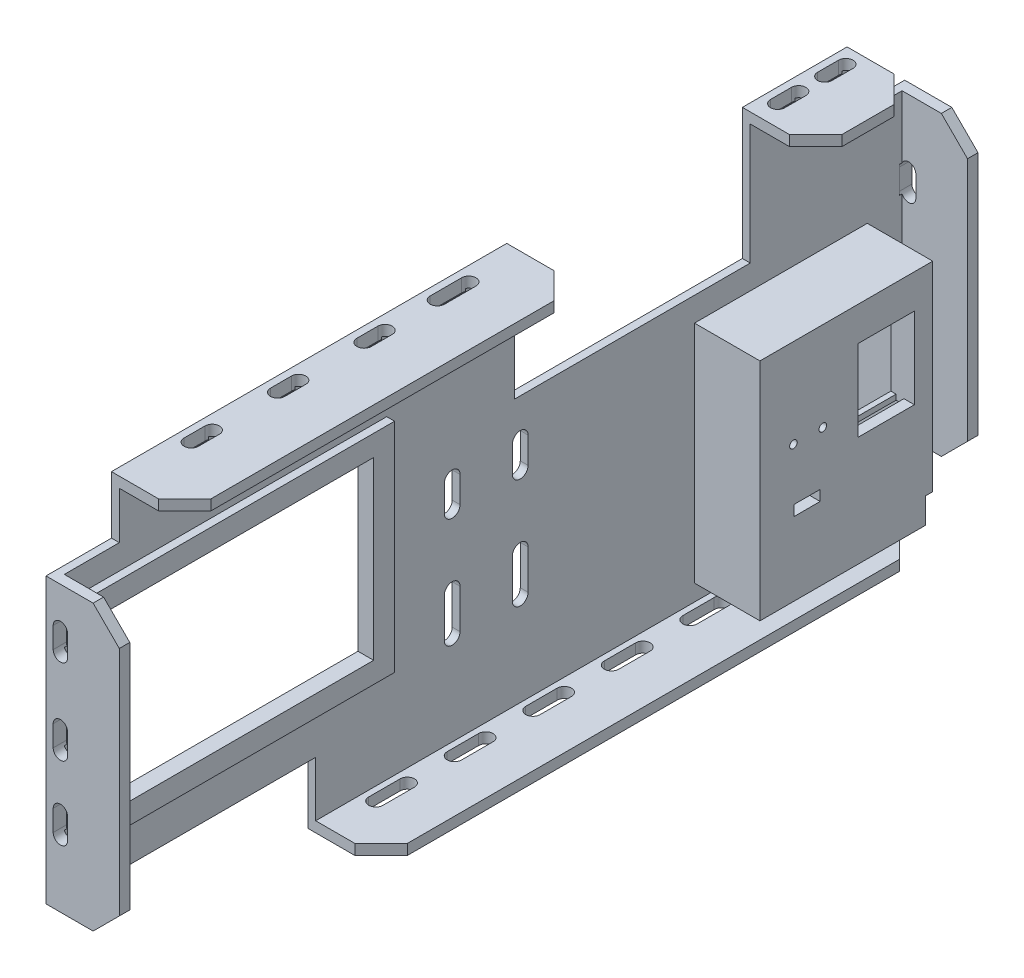
SolidWorks part; units mm, degrees
ref_plane "前视基准面" through (0, 0, 0) normal (0, 0, 1) x (1, 0, 0)
ref_plane "上视基准面" through (0, 0, 0) normal (0, 1, 0) x (1, 0, 0)
ref_plane "右视基准面" through (0, 0, 0) normal (1, 0, 0) x (0, 0, -1)
other "Configuration Table"
sketch "草图1" plane through (0, 0, 0) normal (1, 0, 0) x (0, 0, -1)
  line L0 (10, 87) -> (70, 87)
  line L1 (0, 0) -> (80, 0)
  line L2 (0, 0) -> (0, 97)
  line L3 (0, 97) -> (80, 97)
  line L4 (80, 0) -> (80, 97)
  line L5 (70, 10) -> (70, 87)
  line L6 (10, 10) -> (70, 10)
  line L7 (10, 10) -> (10, 87)
  dimension "D1" = 97
  dimension "D2" = 80
  dimension "D3" = 10
extrude "凸台-拉伸1" add sketch "草图1" along normal blind 6
sketch "草图2" plane through (6, 0, 0) normal (1, 0, 0) x (0, 0, -1)
  line L0 (80, 97) -> (0, 97) construction
  line L1 (10, 87) -> (70, 87)
  line L2 (10, 87) -> (10, 97)
  line L3 (10, 97) -> (70, 97)
  line L4 (70, 87) -> (70, 97)
  line L5 (0, 0) -> (80, 0) construction
  line L6 (10, 10) -> (70, 10)
  line L7 (10, 10) -> (10, 0)
  line L8 (10, 0) -> (70, 0)
  line L9 (70, 10) -> (70, 0)
extrude "凸台-拉伸2" add sketch "草图2" along normal blind 25
sketch "草图3" plane through (31, 0, 0) normal (1, 0, 0) x (0, 0, -1)
  line L1 (10, 87) -> (70, 87)
  line L2 (10, 87) -> (10, 10)
  line L3 (10, 10) -> (70, 10)
  line L4 (70, 87) -> (70, 10)
extrude "凸台-拉伸3" add sketch "草图3" against normal blind 4
sketch "草图4" plane through (27, 0, 0) normal (-1, 0, 0) x (0, 0, 1)
  line L0 (-70, 10) -> (-70, 87) construction
  line L1 (-66, 46) -> (-44.5, 46)
  line L2 (-66, 46) -> (-66, 77)
  line L3 (-66, 77) -> (-44.5, 77)
  line L4 (-44.5, 46) -> (-44.5, 77)
  line L5 (-70, 87) -> (-10, 87) construction
  dimension "D1" = 4
  dimension "D2" = 21.5
  dimension "D3" = 31
  dimension "D4" = 10
extrude "切除-拉伸1" cut sketch "草图4" against normal blind 4
sketch "草图5" plane through (27, 0, 0) normal (-1, 0, 0) x (0, 0, 1)
  line L0 (-66, 46) -> (-44.5, 46) construction
  line L1 (-44.5, 46) -> (-44.5, 77) construction
  line L2 (-66, 77) -> (-66, 46) construction
  line L3 (-44.5, 77) -> (-66, 77) construction
  line L4 (-66, 46) -> (-44.5, 46)
  line L5 (-44.5, 46) -> (-44.5, 77)
  line L6 (-66, 77) -> (-66, 46)
  line L7 (-44.5, 77) -> (-66, 77)
  line L8 (-68, 44) -> (-42.5, 44)
  line L9 (-42.5, 44) -> (-42.5, 79)
  line L10 (-42.5, 79) -> (-68, 79)
  line L11 (-68, 79) -> (-68, 44)
  dimension "D1" = 2
extrude "凸台-拉伸4" add sketch "草图5" along normal blind 5
sketch "草图6" plane through (0, 44, 0) normal (0, -1, 0) x (1, 0, 0)
  line L0 (22, -68) -> (27, -68) construction
  line L1 (24, -44.5) -> (27, -44.5)
  line L2 (24, -44.5) -> (24, -66)
  line L3 (24, -66) -> (27, -66)
  line L4 (27, -44.5) -> (27, -66)
  line L5 (22, -42.5) -> (27, -42.5) construction
  line L6 (22, -68) -> (22, -42.5) construction
  dimension "D1" = 2
  dimension "D2" = 2
  dimension "D3" = 2
  dimension "D4" = 3
extrude "切除-拉伸2" cut sketch "草图6" against normal blind 37
sketch "草图7" plane through (27, 0, 0) normal (-1, 0, 0) x (0, 0, 1)
  line L0 (-42.5, 44) -> (-42.5, 79) construction
  line L1 (-34.5, 44) -> (-16.3, 44)
  line L2 (-34.5, 44) -> (-34.5, 74.1)
  line L3 (-34.5, 74.1) -> (-16.3, 74.1)
  line L4 (-16.3, 44) -> (-16.3, 74.1)
  dimension "D1" = 18.2
  dimension "D2" = 30.1
  dimension "D3" = 8
  dimension "D4" = 44
extrude "切除-拉伸3" cut sketch "草图7" against normal blind 1.5
sketch "草图8" plane through (28.5, 0, 0) normal (-1, 0, 0) x (0, 0, 1)
  line L0 (-34.5, 44) -> (-16.3, 44) construction
  line L1 (-34.5, 44) -> (-16.3, 44) construction
  line L2 (-34.5, 74.1) -> (-34.5, 44) construction
  line L3 (-16.3, 44) -> (-16.3, 74.1) construction
  circle A0 centre (-31, 56) radius 1.45
  circle A1 centre (-19.8, 56) radius 1.45
  dimension "D1" = 12
  dimension "D3" = 2.9
  dimension "D4" = 2.9
  dimension "D2" = 12
  dimension "D5" = 3.5
  dimension "D6" = 3.5
extrude "切除-拉伸5" cut sketch "草图8" against normal blind 4.5
fillet "圆角1" radius 3 1 edges at (0, 0, -40)
fillet "圆角2" radius 3 1 edges at (0, 97, -40)
sketch "草图9" plane through (0, 97, 0) normal (0, 1, 0) x (1, 0, 0)
  line L0 (0, 0) -> (0, 80) construction
  line L1 (31, 70) -> (6, 70) construction
  circle A0 centre (6.2, 54) radius 2.75
  circle A1 centre (6.2, 46) radius 2.75
  circle A2 centre (6.2, 36) radius 2.75
  circle A3 centre (6.2, 28) radius 2.75
  dimension "D1" = 6.2
  dimension "D3" = 5.5
  dimension "D2" = 16
  dimension "D4" = 8
  dimension "D5" = 10
  dimension "D6" = 8
extrude "切除-拉伸6" cut sketch "草图9" against normal blind 10
sketch "草图10" plane through (0, 0, 0) normal (-1, 0, 0) x (0, 0, 1)
  line L1 (-70, 87) -> (-10, 87)
  line L2 (-70, 87) -> (-70, 92)
  line L3 (-70, 92) -> (-10, 92)
  line L4 (-10, 87) -> (-10, 92)
  dimension "D1" = 5
extrude "切除-拉伸7" cut sketch "草图10" against normal blind 20
sketch "草图11" plane through (0, 0, 0) normal (-1, 0, 0) x (0, 0, 1)
  line L0 (-10, 92) -> (-10, 10) construction
  line L1 (-70, 10) -> (-10, 10)
  line L2 (-70, 10) -> (-70, 20)
  line L3 (-70, 20) -> (-10, 20)
  line L4 (-10, 10) -> (-10, 20)
  dimension "D1" = 10
extrude "凸台-拉伸5" add sketch "草图11" against normal blind 5
sketch "草图12" plane through (0, 0, 0) normal (-1, 0, 0) x (0, 0, 1)
  line L0 (0, 0) -> (-80, 0) construction
  line L1 (0, 94) -> (0, 3) construction
  circle A0 centre (-61, 14) radius 2.7
  circle A1 centre (-46, 14) radius 2.7
  circle A2 centre (-30, 14) radius 2.7
  circle A3 centre (-15, 14) radius 2.7
  dimension "D1" = 14
  dimension "D2" = 5.4
  dimension "D4" = 5.4
  dimension "D5" = 5.4
  dimension "D6" = 5.4
  dimension "D3" = 15
  dimension "D7" = 15
  dimension "D8" = 15
  dimension "D9" = 16
extrude "切除-拉伸8" cut sketch "草图12" against normal blind 5
sketch "草图13" plane through (0, 0, -70) normal (0, 0, -1) x (-1, 0, 0)
  line L1 (-6, 10) -> (-27, 10)
  line L2 (-6, 10) -> (-6, 7)
  line L3 (-6, 7) -> (-27, 7)
  line L4 (-27, 10) -> (-27, 7)
  dimension "D1" = 3
extrude "切除-拉伸9" cut sketch "草图13" against normal blind 80
sketch "草图14" plane through (0, 0, 0) normal (-1, 0, 0) x (0, 0, 1)
  line L1 (-121.2338, 126.064) -> (53.7432, 126.064)
  line L2 (-121.2338, 126.064) -> (-121.2338, -60.5781)
  line L3 (-121.2338, -60.5781) -> (53.7432, -60.5781)
  line L4 (53.7432, 126.064) -> (53.7432, -60.5781)
extrude "切除-拉伸11" cut sketch "草图14" against normal blind 22
sketch "草图15" plane through (22, 0, 0) normal (-1, 0, 0) x (0, 0, 1)
  line L4 (-10, 87) -> (-10, 97)
  line L5 (-10, 97) -> (-70, 97)
  line L6 (-70, 97) -> (-70, 87)
  line L7 (-70, 87) -> (-10, 87)
  line L8 (-10, 87) -> (-10, 97)
  line L9 (-10, 97) -> (-70, 97)
  line L10 (-70, 97) -> (-70, 87)
  line L11 (-70, 87) -> (-10, 87)
  line L12 (-70, 0) -> (-10, 0)
  line L13 (-10, 0) -> (-10, 7)
  line L14 (-10, 7) -> (-70, 7)
  line L15 (-70, 7) -> (-70, 0)
  line L16 (-70, 0) -> (-10, 0)
  line L17 (-10, 0) -> (-10, 7)
  line L18 (-10, 7) -> (-70, 7)
  line L19 (-70, 7) -> (-70, 0)
  dimension "D1" = 0
  dimension "D2" = 0
extrude "切除-拉伸12" cut sketch "草图15" against normal blind 22
sketch "草图19" plane through (31, 0, 0) normal (1, 0, 0) x (0, 0, -1)
  line L0 (86.2882, 145.23) -> (-233.7118, 145.23)
  line L1 (90.2882, -6.27) -> (-237.7118, -6.27)
  line L2 (90.2882, -6.27) -> (90.2882, 149.23)
  line L3 (90.2882, 149.23) -> (-237.7118, 149.23)
  line L4 (-237.7118, -6.27) -> (-237.7118, 149.23)
  line L5 (-233.7118, -2.27) -> (-233.7118, 145.23)
  line L6 (86.2882, -2.27) -> (-233.7118, -2.27)
  line L7 (86.2882, -2.27) -> (86.2882, 145.23)
  dimension "D1" = 155.5
  dimension "D2" = 328
  dimension "D3" = 4
extrude "凸台-拉伸6" add sketch "草图19" against normal blind 28 separate body
sketch "草图20" plane through (31, 0, 0) normal (1, 0, 0) x (0, 0, -1)
  line L0 (73, 90) -> (7, 90)
  line L1 (7, 90) -> (7, 4)
  line L2 (7, 4) -> (73, 4)
  line L3 (73, 4) -> (73, 90)
  line L4 (70, 7) -> (70, 87)
  line L5 (70, 87) -> (10, 87)
  line L6 (10, 87) -> (10, 7)
  line L7 (10, 7) -> (70, 7)
  line L8 (70, 7) -> (70, 87)
  line L9 (70, 87) -> (10, 87)
  line L10 (10, 87) -> (10, 7)
  line L11 (10, 7) -> (70, 7)
  dimension "D1" = 0
  dimension "D2" = 3
extrude "凸台-拉伸7" add sketch "草图20" against normal blind 28
sketch "草图21" plane through (3, 0, 0) normal (-1, 0, 0) x (0, 0, 1)
  line L4 (-90.2882, 149.23) -> (-90.2882, -6.27)
  line L5 (-90.2882, -6.27) -> (237.7118, -6.27)
  line L6 (237.7118, -6.27) -> (237.7118, 149.23)
  line L7 (237.7118, 149.23) -> (-90.2882, 149.23)
  line L8 (-90.2882, 149.23) -> (-90.2882, -6.27)
  line L9 (-90.2882, -6.27) -> (237.7118, -6.27)
  line L10 (237.7118, -6.27) -> (237.7118, 149.23)
  line L11 (237.7118, 149.23) -> (-90.2882, 149.23)
  line L12 (-73, 90) -> (-73, 4)
  line L13 (-73, 4) -> (-7, 4)
  line L14 (-7, 4) -> (-7, 90)
  line L15 (-7, 90) -> (-73, 90)
  line L16 (-73, 90) -> (-73, 4)
  line L17 (-73, 4) -> (-7, 4)
  line L18 (-7, 4) -> (-7, 90)
  line L19 (-7, 90) -> (-73, 90)
  dimension "D1" = 0
  dimension "D2" = 0
extrude "凸台-拉伸8" add sketch "草图21" against normal blind 3
sketch "草图22" plane through (6, 0, 0) normal (1, 0, 0) x (0, 0, -1)
  line L0 (-85.5598, 84.73) -> (-85.5598, 74.73) construction
  line L1 (-82.5598, 84.73) -> (-82.5598, 74.73)
  line L2 (-88.5598, 84.73) -> (-88.5598, 74.73)
  line L3 (-85.5598, 32.73) -> (-85.5598, 47.73) construction
  line L4 (-88.5598, 32.73) -> (-88.5598, 47.73)
  line L5 (-82.5598, 32.73) -> (-82.5598, 47.73)
  line L6 (-59.5598, 74.7258) -> (-59.5598, 84.7258) construction
  line L7 (-62.5598, 74.7258) -> (-62.5598, 84.7258)
  line L8 (-56.5598, 74.7258) -> (-56.5598, 84.7258)
  line L9 (-59.5598, 32.73) -> (-59.5598, 47.73) construction
  line L10 (-62.5598, 32.73) -> (-62.5598, 47.73)
  line L11 (-56.5598, 32.73) -> (-56.5598, 47.73)
  line L12 (-233.7118, -2.27) -> (86.2882, -2.27) construction
  arc A0 (-82.5598, 84.73) -> (-88.5598, 84.73) centre (-85.5598, 84.73) ccw
  arc A1 (-88.5598, 74.73) -> (-82.5598, 74.73) centre (-85.5598, 74.73) ccw
  arc A2 (-88.5598, 32.73) -> (-82.5598, 32.73) centre (-85.5598, 32.73) ccw
  arc A3 (-82.5598, 47.73) -> (-88.5598, 47.73) centre (-85.5598, 47.73) ccw
  arc A4 (-62.5598, 74.7258) -> (-56.5598, 74.7258) centre (-59.5598, 74.7258) ccw
  arc A5 (-56.5598, 84.7258) -> (-62.5598, 84.7258) centre (-59.5598, 84.7258) ccw
  arc A6 (-62.5598, 32.73) -> (-56.5598, 32.73) centre (-59.5598, 32.73) ccw
  arc A7 (-56.5598, 47.73) -> (-62.5598, 47.73) centre (-59.5598, 47.73) ccw
  point P2 (-85.5598, 79.73)
  point P7 (-85.5598, 40.23)
  point P14 (-59.5598, 79.7258)
  point P21 (-59.5598, 40.23)
  dimension "D4" = 52
  dimension "D7" = 3
  dimension "D8" = 3
  dimension "D9" = 3
  dimension "D10" = 3
  dimension "D1" = 26
  dimension "D2" = 10
  dimension "D3" = 10
  dimension "D5" = 15
  dimension "D6" = 15
  dimension "D11" = 35
extrude "切除-拉伸13" cut sketch "草图22" against normal blind 3
sketch "草图24" plane through (6, 0, 0) normal (1, 0, 0) x (0, 0, -1)
  line L0 (-88.5598, 47.73) -> (-88.5598, 32.73) construction
  line L1 (-118.5598, 42.73) -> (-223.8598, 42.73)
  line L2 (-118.5598, 42.73) -> (-118.5598, 109.83)
  line L3 (-118.5598, 109.83) -> (-223.8598, 109.83)
  line L4 (-223.8598, 42.73) -> (-223.8598, 109.83)
  line L5 (-233.7118, -2.27) -> (86.2882, -2.27) construction
  dimension "D1" = 105.3
  dimension "D2" = 67.1
  dimension "D3" = 30
  dimension "D4" = 45
extrude "切除-拉伸15" cut sketch "草图24" against normal blind 3
sketch "草图26" plane through (6, 0, 0) normal (1, 0, 0) x (0, 0, -1)
  line L0 (-118.5598, 42.73) -> (-118.5598, 109.83) construction
  line L1 (-118.5598, 42.73) -> (-118.5598, 109.83)
  line L3 (-118.5598, 109.83) -> (-223.8598, 109.83) construction
  line L4 (-233.7118, -2.27) -> (86.2882, -2.27)
  line L5 (86.2882, -2.27) -> (86.2882, 145.23)
  line L6 (86.2882, 145.23) -> (-233.7118, 145.23)
  line L7 (-233.7118, 145.23) -> (-233.7118, -2.27)
  line L8 (-233.7118, -2.27) -> (86.2882, -2.27)
  line L9 (86.2882, -2.27) -> (86.2882, 145.23)
  line L10 (86.2882, 145.23) -> (-233.7118, 145.23)
  line L11 (-233.7118, 145.23) -> (-233.7118, -2.27)
  line L12 (-118.5598, 109.83) -> (-223.8598, 109.83)
  line L13 (-223.8598, 42.73) -> (-118.5598, 42.73) construction
  line L14 (-223.8598, 109.83) -> (-223.8598, 42.73) construction
  line L15 (-223.8598, 42.73) -> (-118.5598, 42.73)
  line L16 (-223.8598, 109.83) -> (-223.8598, 42.73)
  line L17 (-110.5598, 117.83) -> (-231.8598, 117.83)
  line L18 (-231.8598, 117.83) -> (-231.8598, 34.73)
  line L19 (-231.8598, 34.73) -> (-110.5598, 34.73)
  line L20 (-110.5598, 34.73) -> (-110.5598, 117.83)
  line M7 (-223.8598, 109.83) -> (-118.5598, 109.83)
  line M8 (-118.5598, 109.83) -> (-118.5598, 42.73)
  line M9 (-118.5598, 42.73) -> (-223.8598, 42.73)
  line M10 (-223.8598, 42.73) -> (-223.8598, 109.83)
  dimension "D1" = 0
  dimension "D2" = 8
extrude "凸台-拉伸11" add sketch "草图26" along normal blind 3 contours L19 L20 L17 L18 M10 M7 M8 M9
sketch "草图27" plane through (31, 0, 0) normal (1, 0, 0) x (0, 0, -1)
  line L1 (-237.7118, -6.27) -> (-137.7118, -6.27)
  line L2 (-237.7118, -6.27) -> (-237.7118, 18.73)
  line L3 (-237.7118, 18.73) -> (-137.7118, 18.73)
  line L4 (-137.7118, -6.27) -> (-137.7118, 18.73)
  dimension "D1" = 25
  dimension "D2" = 100
extrude "切除-拉伸16" cut sketch "草图27" against normal blind 36
sketch "草图28" plane through (31, 0, 0) normal (1, 0, 0) x (0, 0, -1)
  line L1 (90.2882, -6.27) -> (70.2882, -6.27)
  line L2 (90.2882, -6.27) -> (90.2882, 13.73)
  line L3 (90.2882, 13.73) -> (70.2882, 13.73)
  line L4 (70.2882, -6.27) -> (70.2882, 13.73)
  dimension "D1" = 20
  dimension "D2" = 20
extrude "切除-拉伸17" cut sketch "草图28" against normal blind 36
sketch "草图29" plane through (31, 0, 0) normal (1, 0, 0) x (0, 0, -1)
  line L1 (90.2882, 149.23) -> (68.2882, 149.23)
  line L2 (90.2882, 149.23) -> (90.2882, 127.23)
  line L3 (90.2882, 127.23) -> (68.2882, 127.23)
  line L4 (68.2882, 149.23) -> (68.2882, 127.23)
  line L5 (-237.7118, 149.23) -> (-212.7118, 149.23)
  line L6 (-237.7118, 149.23) -> (-237.7118, 127.23)
  line L7 (-237.7118, 127.23) -> (-212.7118, 127.23)
  line L8 (-212.7118, 149.23) -> (-212.7118, 127.23)
  dimension "D1" = 22
  dimension "D2" = 22
  dimension "D3" = 25
  dimension "D4" = 22
extrude "切除-拉伸18" cut sketch "草图29" against normal blind 36
sketch "草图31" plane through (31, 0, 0) normal (1, 0, 0) x (0, 0, -1)
  line L0 (68.2882, 149.23) -> (-212.7118, 149.23) construction
  line L1 (28.2882, 149.23) -> (-61.7118, 149.23)
  line L2 (28.2882, 149.23) -> (28.2882, 99.23)
  line L3 (28.2882, 99.23) -> (-61.7118, 99.23)
  line L4 (-61.7118, 149.23) -> (-61.7118, 99.23)
  line L5 (90.2882, 13.73) -> (90.2882, 127.23) construction
  dimension "D1" = 62
  dimension "D2" = 90
  dimension "D3" = 50
extrude "切除-拉伸19" cut sketch "草图31" against normal blind 36
sketch "草图32" plane through (27, 0, 0) normal (-1, 0, 0) x (0, 0, 1)
  line L0 (-34.5, 44) -> (-16.3, 44) construction
  line L1 (-30, 36) -> (-20, 36)
  line L2 (-30, 36) -> (-30, 32)
  line L3 (-30, 32) -> (-20, 32)
  line L4 (-20, 36) -> (-20, 32)
  line L5 (-10, 87) -> (-10, 7) construction
  dimension "D1" = 8
  dimension "D2" = 4
  dimension "D3" = 10
  dimension "D4" = 10
extrude "切除-拉伸20" cut sketch "草图32" against normal blind 36
sketch "草图33" plane through (0, 149.23, 0) normal (0, 1, 0) x (1, 0, 0)
  line L0 (8.5, 62.2882) -> (8.5, 54.2882) construction
  line L3 (11.25, 62.2882) -> (11.25, 54.2882)
  line L6 (8.5, -81.7118) -> (8.5, -93.7118) construction
  line L7 (11.25, -81.7118) -> (11.25, -93.7118)
  line L8 (5.75, -81.7118) -> (5.75, -93.7118)
  line L9 (8.5, -113.7118) -> (8.5, -121.7118) construction
  line L10 (11.25, -113.7118) -> (11.25, -121.7118)
  line L11 (5.75, -113.7118) -> (5.75, -121.7118)
  line L12 (8.5, -146.7118) -> (8.5, -154.7118) construction
  line L13 (11.25, -146.7118) -> (11.25, -154.7118)
  line L14 (5.75, -146.7118) -> (5.75, -154.7118)
  line L15 (8.5, -179.7118) -> (8.5, -187.7118) construction
  line L16 (11.25, -179.7118) -> (11.25, -187.7118)
  line L17 (5.75, -179.7118) -> (5.75, -187.7118)
  line L18 (3, -61.7118) -> (3, -212.7118) construction
  line L19 (3, -212.7118) -> (31, -212.7118) construction
  line L20 (5.75, 62.2882) -> (5.75, 54.2882)
  line L22 (8.5, 44.2882) -> (8.5, 36.2882) construction
  line L23 (11.25, 44.2882) -> (11.25, 36.2882)
  line L24 (5.75, 44.2882) -> (5.75, 36.2882)
  line L25 (3, 68.2882) -> (3, 28.2882) construction
  line L26 (3, 68.2882) -> (31, 68.2882) construction
  line L27 (3, 28.2882) -> (31, 28.2882) construction
  arc A4 (11.25, -81.7118) -> (5.75, -81.7118) centre (8.5, -81.7118) ccw
  arc A5 (5.75, -93.7118) -> (11.25, -93.7118) centre (8.5, -93.7118) ccw
  arc A6 (11.25, -113.7118) -> (5.75, -113.7118) centre (8.5, -113.7118) ccw
  arc A7 (5.75, -121.7118) -> (11.25, -121.7118) centre (8.5, -121.7118) ccw
  arc A8 (11.25, -146.7118) -> (5.75, -146.7118) centre (8.5, -146.7118) ccw
  arc A9 (5.75, -154.7118) -> (11.25, -154.7118) centre (8.5, -154.7118) ccw
  arc A10 (11.25, -179.7118) -> (5.75, -179.7118) centre (8.5, -179.7118) ccw
  arc A11 (5.75, -187.7118) -> (11.25, -187.7118) centre (8.5, -187.7118) ccw
  arc A12 (11.25, 62.2882) -> (5.75, 62.2882) centre (8.5, 62.2882) ccw
  arc A13 (5.75, 54.2882) -> (11.25, 54.2882) centre (8.5, 54.2882) ccw
  arc A14 (11.25, 44.2882) -> (5.75, 44.2882) centre (8.5, 44.2882) ccw
  arc A15 (5.75, 36.2882) -> (11.25, 36.2882) centre (8.5, 36.2882) ccw
  point P2 (5.75, 58.3197)
  point P3 (8.5, 58.2882)
  point P7 (5.75, 37.9476)
  point P9 (8.5, 40.2882)
  point P14 (8.5, -87.7118)
  point P21 (8.5, -117.7118)
  point P28 (8.5, -150.7118)
  point P35 (8.5, -183.7118)
  point P52 (0, 0)
  dimension "D9" = 25
  dimension "D1" = 5.5
  dimension "D2" = 5.5
  dimension "D3" = 8
  dimension "D4" = 25
  dimension "D5" = 25
  dimension "D6" = 8
  dimension "D7" = 5.5
  dimension "D8" = 8
  dimension "D10" = 12
  dimension "D11" = 20
  dimension "D12" = 5.5
  dimension "D13" = 5.5
  dimension "D14" = 8
  dimension "D15" = 6
  dimension "D16" = 8
  dimension "D17" = 8
extrude "切除-拉伸21" cut sketch "草图33" against normal blind 5
sketch "草图34" plane through (0, 0, -90.2882) normal (0, 0, -1) x (-1, 0, 0)
  line L0 (-8.5, 102.23) -> (-8.5, 94.23) construction
  line L1 (-5.75, 102.23) -> (-5.75, 94.23)
  line L2 (-11.25, 102.23) -> (-11.25, 94.23)
  line L3 (-8.5, 64.73) -> (-8.5, 56.73) construction
  line L4 (-5.75, 64.73) -> (-5.75, 56.73)
  line L5 (-11.25, 64.73) -> (-11.25, 56.73)
  line L6 (-8.5, 31.73) -> (-8.5, 23.73) construction
  line L7 (-5.75, 31.73) -> (-5.75, 23.73)
  line L8 (-11.25, 31.73) -> (-11.25, 23.73)
  line L9 (-3, 13.73) -> (-3, 127.23) construction
  line L10 (-3, 13.73) -> (-31, 13.73) construction
  line L11 (-3, 127.23) -> (-31, 127.23) construction
  arc A0 (-5.75, 102.23) -> (-11.25, 102.23) centre (-8.5, 102.23) ccw
  arc A1 (-11.25, 94.23) -> (-5.75, 94.23) centre (-8.5, 94.23) ccw
  arc A2 (-5.75, 64.73) -> (-11.25, 64.73) centre (-8.5, 64.73) ccw
  arc A3 (-11.25, 56.73) -> (-5.75, 56.73) centre (-8.5, 56.73) ccw
  arc A4 (-5.75, 31.73) -> (-11.25, 31.73) centre (-8.5, 31.73) ccw
  arc A5 (-11.25, 23.73) -> (-5.75, 23.73) centre (-8.5, 23.73) ccw
  point P2 (-8.5, 98.23)
  point P7 (-8.5, 60.73)
  point P14 (-8.5, 27.73)
  dimension "D1" = 8
  dimension "D2" = 8
  dimension "D3" = 8
  dimension "D4" = 5.5
  dimension "D5" = 5.5
  dimension "D6" = 5.5
  dimension "D7" = 5.5
  dimension "D8" = 10
  dimension "D9" = 25
  dimension "D10" = 25
extrude "切除-拉伸22" cut sketch "草图34" against normal blind 5
sketch "草图35" plane through (0, 0, 237.7118) normal (0, 0, 1) x (1, 0, 0)
  line L0 (8.5, 112.23) -> (8.5, 104.23) construction
  line L1 (11.25, 112.23) -> (11.25, 104.23)
  line L2 (5.75, 112.23) -> (5.75, 104.23)
  line L3 (8.5, 79.73) -> (8.5, 71.73) construction
  line L4 (11.25, 79.73) -> (11.25, 71.73)
  line L5 (5.75, 79.73) -> (5.75, 71.73)
  line L6 (8.5, 51.73) -> (8.5, 43.73) construction
  line L7 (11.25, 51.73) -> (11.25, 43.73)
  line L8 (5.75, 51.73) -> (5.75, 43.73)
  line L9 (3, 127.23) -> (3, 18.73) construction
  line L10 (3, 18.73) -> (31, 18.73) construction
  line L11 (3, 127.23) -> (31, 127.23) construction
  arc A0 (11.25, 112.23) -> (5.75, 112.23) centre (8.5, 112.23) ccw
  arc A1 (5.75, 104.23) -> (11.25, 104.23) centre (8.5, 104.23) ccw
  arc A2 (11.25, 79.73) -> (5.75, 79.73) centre (8.5, 79.73) ccw
  arc A3 (5.75, 71.73) -> (11.25, 71.73) centre (8.5, 71.73) ccw
  arc A4 (11.25, 51.73) -> (5.75, 51.73) centre (8.5, 51.73) ccw
  arc A5 (5.75, 43.73) -> (11.25, 43.73) centre (8.5, 43.73) ccw
  point P2 (8.5, 108.23)
  point P7 (8.5, 75.73)
  point P14 (8.5, 47.73)
  dimension "D1" = 8
  dimension "D2" = 8
  dimension "D3" = 8
  dimension "D4" = 5.5
  dimension "D5" = 5.5
  dimension "D6" = 5.5
  dimension "D7" = 5.5
  dimension "D8" = 25
  dimension "D9" = 20
  dimension "D10" = 15
extrude "切除-拉伸23" cut sketch "草图35" against normal blind 5
sketch "草图36" plane through (0, -6.27, 0) normal (0, -1, 0) x (1, 0, 0)
  line L0 (11, 119.7118) -> (11, 107.7118) construction
  line L1 (13.75, 119.7118) -> (13.75, 107.7118)
  line L2 (8.25, 119.7118) -> (8.25, 107.7118)
  line L3 (3, 137.7118) -> (3, -70.2882) construction
  line L4 (3, 137.7118) -> (31, 137.7118) construction
  line L5 (11, 89.7118) -> (11, 77.7118) construction
  line L6 (13.75, 89.7118) -> (13.75, 77.7118)
  line L7 (8.25, 89.7118) -> (8.25, 77.7118)
  line L8 (11, 59.7118) -> (11, 47.7118) construction
  line L9 (13.75, 59.7118) -> (13.75, 47.7118)
  line L10 (8.25, 59.7118) -> (8.25, 47.7118)
  line L11 (11, 29.7118) -> (11, 17.7118) construction
  line L12 (13.75, 29.7118) -> (13.75, 17.7118)
  line L13 (8.25, 29.7118) -> (8.25, 17.7118)
  line L14 (11, -0.2882) -> (11, -12.2882) construction
  line L15 (13.75, -0.2882) -> (13.75, -12.2882)
  line L16 (8.25, -0.2882) -> (8.25, -12.2882)
  line L17 (11, -30.2882) -> (11, -42.2882) construction
  line L18 (13.75, -30.2882) -> (13.75, -42.2882)
  line L19 (8.25, -30.2882) -> (8.25, -42.2882)
  arc A0 (13.75, 119.7118) -> (8.25, 119.7118) centre (11, 119.7118) ccw
  arc A1 (8.25, 107.7118) -> (13.75, 107.7118) centre (11, 107.7118) ccw
  arc A2 (13.75, 89.7118) -> (8.25, 89.7118) centre (11, 89.7118) ccw
  arc A3 (8.25, 77.7118) -> (13.75, 77.7118) centre (11, 77.7118) ccw
  arc A4 (13.75, 59.7118) -> (8.25, 59.7118) centre (11, 59.7118) ccw
  arc A5 (8.25, 47.7118) -> (13.75, 47.7118) centre (11, 47.7118) ccw
  arc A6 (13.75, 29.7118) -> (8.25, 29.7118) centre (11, 29.7118) ccw
  arc A7 (8.25, 17.7118) -> (13.75, 17.7118) centre (11, 17.7118) ccw
  arc A8 (13.75, -0.2882) -> (8.25, -0.2882) centre (11, -0.2882) ccw
  arc A9 (8.25, -12.2882) -> (13.75, -12.2882) centre (11, -12.2882) ccw
  arc A10 (13.75, -30.2882) -> (8.25, -30.2882) centre (11, -30.2882) ccw
  arc A11 (8.25, -42.2882) -> (13.75, -42.2882) centre (11, -42.2882) ccw
  point P2 (11, 113.7118)
  point P15 (11, 83.7118)
  point P22 (11, 53.7118)
  point P29 (11, 23.7118)
  point P36 (11, -6.2882)
  point P43 (11, -36.2882)
  dimension "D1" = 8
  dimension "D2" = 5.5
  dimension "D3" = 30
  dimension "D4" = 12
  dimension "D5" = 6
extrude "切除-拉伸24" cut sketch "草图36" against normal blind 5
chamfer "倒角1" distance 10 angle 45 10 edges at (31, -4.27, 137.7118) (31, -4.27, -70.2882) (31, 13.73, -88.2882) (31, 127.23, -88.2882) (31, 147.23, -28.2882) (31, 147.23, -68.2882) (31, 147.23, 61.7118) (31, 147.23, 212.7118) (31, 127.23, 235.7118) (31, 18.73, 235.7118)
